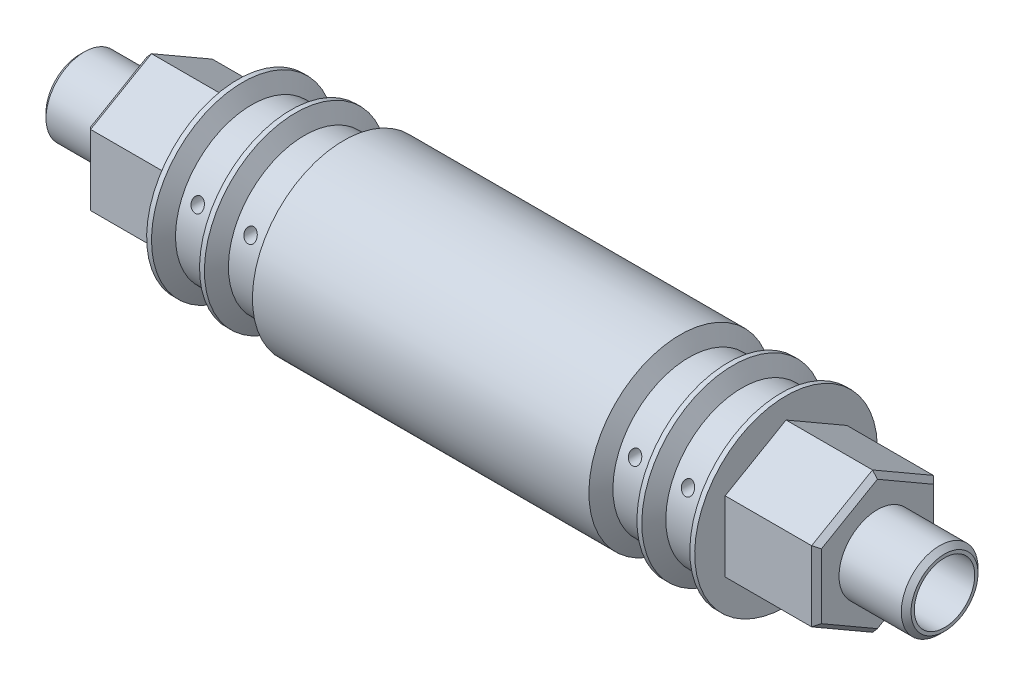
SolidWorks part; units mm, degrees
ref_plane "Front Plane" through (0, 0, 0) normal (0, 0, 1) x (1, 0, 0)
ref_plane "Top Plane" through (0, 0, 0) normal (0, 1, 0) x (1, 0, 0)
ref_plane "Right Plane" through (0, 0, 0) normal (1, 0, 0) x (0, 0, -1)
sketch "Sketch1" plane through (0, 0, 0) normal (0, 0, 1) x (1, 0, 0)
  line L0 (-38.1, 0) -> (38.1, 0) construction
  line L1 (-28.067, 9.525) -> (-27.1505, 7.9375)
  line L2 (-27.1505, 7.9375) -> (-23.9755, 7.9375)
  line L3 (-23.9755, 7.9375) -> (-23.0589, 9.525)
  line L4 (-23.0589, 9.525) -> (-22.5509, 9.525)
  line L5 (-22.5509, 9.525) -> (-21.6344, 7.9375)
  line L6 (-21.6344, 7.9375) -> (-18.4594, 7.9375)
  line L7 (-18.4594, 7.9375) -> (-17.5428, 9.525)
  line L8 (0, 0) -> (0, 25.6809) construction
  line L9 (-17.5428, 9.525) -> (0, 9.525)
  line L10 (-22.8049, 9.525) -> (-22.8049, 0) construction
  line L11 (-28.575, 9.525) -> (-28.575, 4.254)
  line L12 (-28.575, 4.254) -> (-38.1, 4.254)
  line L13 (-38.1, 4.254) -> (-38.1, 4)
  line L14 (-38.1, 0) -> (-28.575, 0)
  line L15 (-28.575, 0) -> (0, 0)
  line L16 (-28.067, 9.525) -> (-28.575, 9.525)
  line L17 (0, 0) -> (0, 9.525)
  line L18 (-38.1, 0) -> (-38.1, -4) construction
  line L19 (-28.575, 4.254) -> (-28.575, 0) construction
  line L20 (-45.1, 4) -> (-45.1, 0)
  line L21 (-45.1, 4) -> (-38.1, 4)
  line L22 (-45.1, 0) -> (-45.1, -4) construction
  line L23 (-38.1, 4) -> (-38.1, 0) construction
  line L24 (-38.1, 0) -> (-45.1, 0)
  line L25 (-45.1, 1.6) -> (-35.275, 1.6)
  line L26 (-35.275, 1.6) -> (-33.675, 0)
  line L27 (-45.1, 1.6) -> (-45.1, -1.6) construction
  line L28 (-48.275, -1.5) -> (-35.275, -1.5) construction
  line L29 (-48.275, -1.5) -> (-48.275, 1.5) construction
  line L30 (-48.275, 1.5) -> (-35.275, 1.5) construction
  line L31 (-35.275, -1.5) -> (-35.275, 1.5) construction
  line L32 (-48.275, -1.5) -> (-35.275, 1.5) construction
  line L33 (-48.275, 1.5) -> (-35.275, -1.5) construction
  point P27 (-41.775, 0)
  point P40 (-45.1, 0)
  dimension "D2" = 3.175
  dimension "D3" = 1.5875
  dimension "D4" = 60
  dimension "D6" = 1.5875
  dimension "D5" = 0.508
  dimension "D7" = 1.5875
  dimension "D8" = 0.508
  dimension "D11" = 9.525
  dimension "D12" = 8
  dimension "D13" = 7
  dimension "D10" = 0.254
  dimension "D9" = 76.2
  dimension "D14" = 9.525
  dimension "D15" = 13
  dimension "D16" = 3
  dimension "D17" = 3.175
  dimension "D18" = 45
  dimension "D19" = 3.2
revolve "Revolve1" add sketch "Sketch1" angle 360 about L0
sketch "Sketch4" plane through (-28.575, 0, 0) normal (-1, 0, 0) x (0, 0, 1)
  line L1 (0, 7.3323) -> (-6.35, 3.6662)
  line L2 (-6.35, 3.6662) -> (-6.35, -3.6662)
  line L3 (-6.35, -3.6662) -> (0, -7.3323)
  line L4 (0, -7.3323) -> (6.35, -3.6662)
  line L5 (6.35, -3.6662) -> (6.35, 3.6662)
  line L6 (6.35, 3.6662) -> (0, 7.3323)
  circle A0 centre (0, 0) radius 6.35 construction
  dimension "D1" = 12.7
extrude "Boss-Extrude4" add sketch "Sketch4" along normal up to surface (9.525 mm away) up to face at (-38.1, -4, 0)
sketch "Sketch6" plane through (0, 0, 0) normal (0, 0, 1) x (1, 0, 0)
  line L0 (-25.563, 7.9375) -> (-25.563, 3.302) construction
  line L1 (-27.1505, 7.9375) -> (-23.9755, 7.9375) construction
  line L2 (-20.0469, 7.9375) -> (-20.0469, 3.302) construction
  line L3 (-21.6344, 7.9375) -> (-18.4594, 7.9375) construction
  circle A0 centre (-25.563, 3.302) radius 0.635
  circle A1 centre (-20.0469, 3.302) radius 0.635
  point P0 (-25.3239, 3.301)
  dimension "D1" = 1.27
  dimension "D2" = 3.302
extrude "Cut-Extrude1" cut sketch "Sketch6" against normal through all both and the other way through all
chamfer "Chamfer2" distance 0.508 angle 45 6 edges at (-38.1, 0, 6.35) (-38.1, -5.4993, 3.175) (-38.1, -5.4993, -3.175) (-38.1, 0, -6.35) (-38.1, 5.4993, -3.175) (-38.1, 5.4993, 3.175)
chamfer "Chamfer3" distance 0.508 angle 45 1 edges at (-45.1, -4, 0)
mirror "Mirror2" about plane through (0, 0, 0) normal (1, 0, 0) of bodies 107
sketch "Sketch7" plane through (-45.1, 0, 0) normal (-1, 0, 0) x (0, 0, 1)
  circle A0 centre (0, 0) radius 3.15
  dimension "D1" = 6.3
extrude "Cut-Extrude2" cut sketch "Sketch7" against normal through all
equation "\"D12@Sketch1\"=8mm"
equation "\"D19@Sketch1\"=3.2mm"
equation "\"D1@Sketch7\"=6mm+.3mm"
